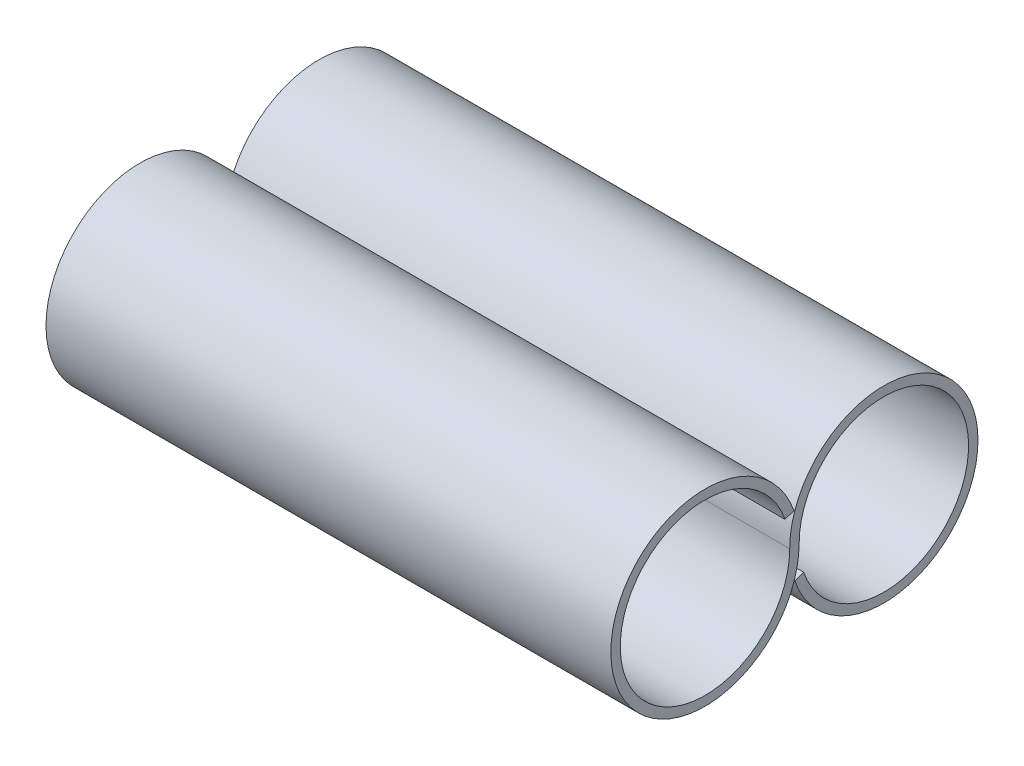
SolidWorks part; units mm, degrees
material "VITON"
ref_plane "Front" through (0, 0, 0) normal (0, 0, 1) x (1, 0, 0)
ref_plane "Top" through (0, 0, 0) normal (0, 1, 0) x (1, 0, 0)
ref_plane "Right" through (0, 0, 0) normal (1, 0, 0) x (0, 0, -1)
sketch "Sketch2" plane through (0, 0, 0) normal (1, 0, 0) x (0, 0, -1)
  line L0 (0.7393, 3.6738) -> (-0.2053, 3.3456)
  line L1 (0.8231, -2.82) -> (1.7701, -2.4987)
  circle A0 centre (-8.7069, 0.3922) radius 9 construction
  circle A1 centre (10.2931, 0.3922) radius 9 construction
  circle A2 centre (-8.7069, 0.3922) radius 10 construction
  circle A3 centre (10.2931, 0.3922) radius 10 construction
  arc A4 (-0.2053, 3.3456) -> (0.2931, 0.3922) centre (-8.7069, 0.3922) ccw
  arc A5 (0.2931, 0.3922) -> (0.8231, -2.82) centre (10.2931, 0.3922) cw
  arc A6 (1.7701, -2.4987) -> (1.2931, 0.3922) centre (10.2931, 0.3922) ccw
  arc A7 (1.2931, 0.3922) -> (0.7393, 3.6738) centre (-8.7069, 0.3922) cw
  dimension "D1" = 18
  dimension "D2" = 18
  dimension "D4" = 20
  dimension "D5" = 20
  dimension "D3" = 19
extrude "Boss-Extrude2" add sketch "Sketch2" along normal blind 60
